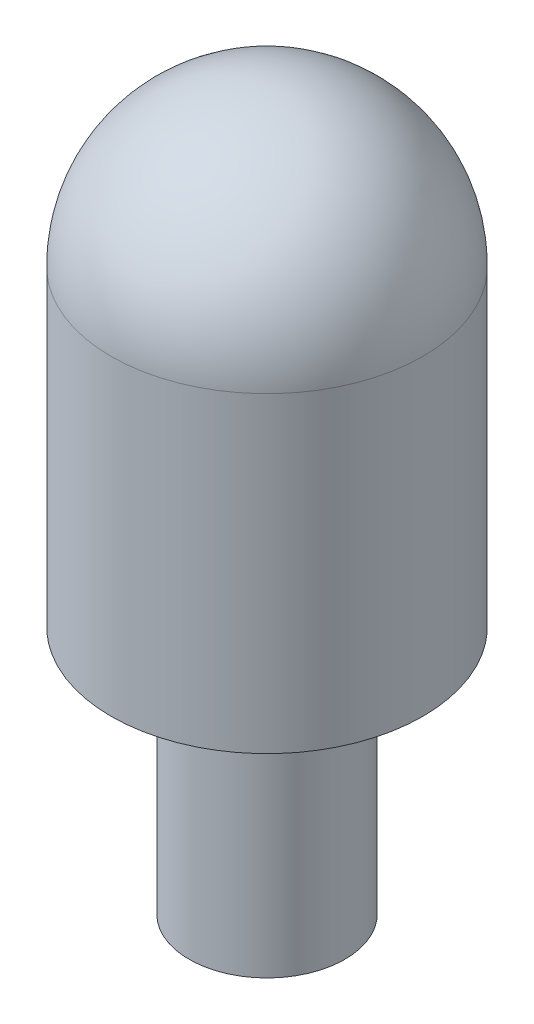
SolidWorks part; units mm, degrees
material "6063-T6，棒材(SS)"
ref_plane "前视基准面" through (0, 0, 0) normal (0, 0, 1) x (1, 0, 0)
ref_plane "上视基准面" through (0, 0, 0) normal (0, 1, 0) x (1, 0, 0)
ref_plane "右视基准面" through (0, 0, 0) normal (1, 0, 0) x (0, 0, -1)
sketch "草图1" plane through (0, 0, 0) normal (1, 0, 0) x (0, 0, -1)
  line L0 (0, 0) -> (0, 27.4213) construction
  line L1 (5, 18) -> (5, 8)
  line L2 (5, 8) -> (2.5, 8)
  line L3 (2.5, 8) -> (2.5, 0)
  line L4 (2.5, 0) -> (0, 0)
  line L5 (0, 0) -> (0, 23)
  arc A0 (5, 18) -> (0, 23) centre (0, 18) ccw
  dimension "D4" = 10
  dimension "D1" = 5
  dimension "D2" = 8
  dimension "D3" = 15
revolve "旋转1" add sketch "草图1" angle 360 about L0
